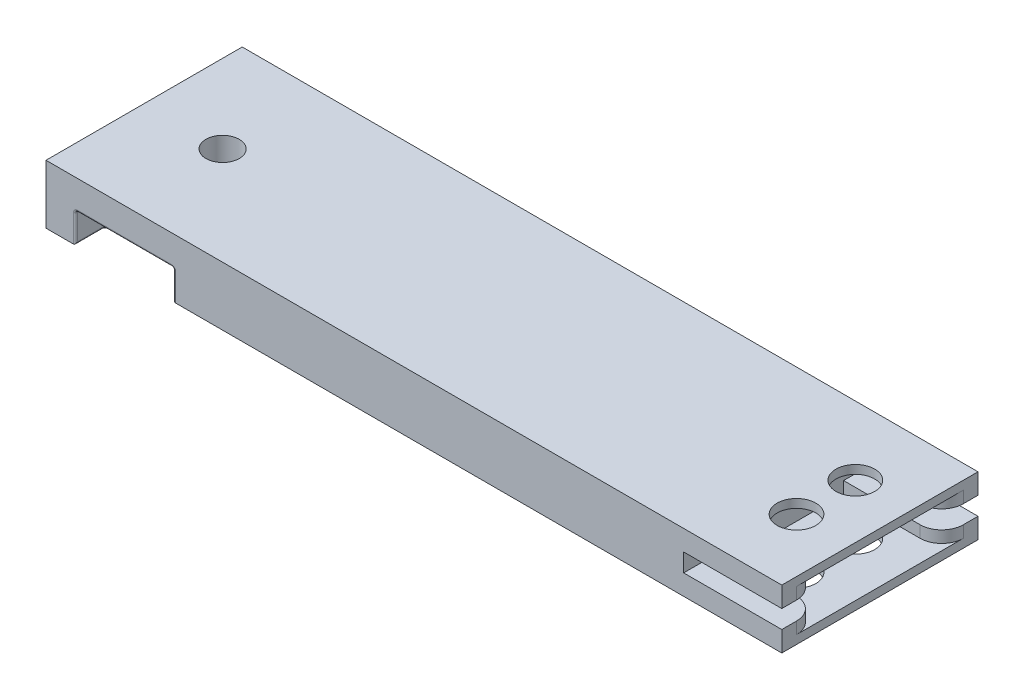
SolidWorks part; units mm, degrees
ref_plane "Front Plane" through (0, 0, 0) normal (0, 0, 1) x (1, 0, 0)
ref_plane "Top Plane" through (0, 0, 0) normal (0, 1, 0) x (1, 0, 0)
ref_plane "Right Plane" through (0, 0, 0) normal (1, 0, 0) x (0, 0, -1)
sketch "Sketch1" plane through (0, 0, 0) normal (1, 0, 0) x (0, 0, -1)
  line L1 (-10, -6) -> (10, -6)
  line L2 (-10, -6) -> (-10, 0)
  line L3 (-10, 0) -> (10, 0)
  line L4 (10, -6) -> (10, 0)
  line L5 (-10, -6) -> (10, 0) construction
  line L6 (-10, 0) -> (10, -6) construction
  point P0 (0, -3)
  dimension "D1" = 20
  dimension "D2" = 6
extrude "Boss-Extrude1" add sketch "Sketch1" along normal blind 75
hole_wizard "M3 Clearance Hole1" positions "Sketch2" profile "Sketch3" hole size "M3" standard "ISO" end condition through all
sketch "Sketch2" plane through (0, 0, 0) normal (0, 1, 0) x (1, 0, 0)
  line L0 (0, 10) -> (0, -10) construction
  point P0 (8, 0)
  dimension "D1" = 8
sketch "Sketch3" plane through (8, 0, 0) normal (1, 0, 0) x (0, 0, 1)
  line L0 (0, 0) -> (0, 6)
  line L1 (0, 6) -> (1.7, 6)
  line L2 (1.7, 6) -> (1.7, 0)
  line L5 (1.7, 0) -> (0, 0)
  line L11 (0, -6.35) -> (0, 107.95) construction
  dimension "Thru Hole Dia." = 3.4
  dimension "Thru Hole Depth" = 6
sketch "Sketch4" plane through (0, 0, 0) normal (0, 1, 0) x (1, 0, 0)
  line L13 (75, 10) -> (75, -10) construction
  circle A0 centre (69.5, 3) radius 1.975
  circle A1 centre (69.5, -3) radius 1.975
  point P10 (69.5, -3)
  point P18 (69.5, 3)
  dimension "D5" = 3.95
  dimension "D6" = 3.95
  dimension "D1" = 5.5
  dimension "D2" = 6
  dimension "D3" = 3
extrude "Cut-Extrude1" cut sketch "Sketch4" against normal through all
sketch "Sketch5" plane through (75, 0, 0) normal (1, 0, 0) x (0, 0, -1)
  line L0 (10, -6) -> (10, 0) construction
  line L1 (-10, -3.925) -> (-6.3, -3.925)
  line L2 (-10, -3.925) -> (-10, -2.075)
  line L3 (-10, -2.075) -> (-6.3, -2.075)
  line L4 (10, -3.925) -> (10, -2.075)
  line L7 (-10, 0) -> (-10, -6) construction
  line L8 (-6.3, -5.125) -> (6.3, -5.125)
  line L9 (-6.3, -5.125) -> (-6.3, -3.925)
  line L10 (-6.3, -0.875) -> (6.3, -0.875)
  line L11 (6.3, -5.125) -> (6.3, -3.925)
  line L15 (-6.3, -2.075) -> (-6.3, -0.875)
  line L18 (6.3, -2.075) -> (10, -2.075)
  line L20 (6.3, -3.925) -> (10, -3.925)
  line L21 (6.3, -2.075) -> (6.3, -0.875)
  point P0 (0, -3)
  point P7 (0, -3)
  point P12 (10, -3)
  point P17 (-10, -3)
  dimension "D1" = 12.6
  dimension "D2" = 1.85
  dimension "D3" = 3
  dimension "D4" = 4.25
extrude "Cut-Extrude2" cut sketch "Sketch5" against normal blind 10
sketch "Sketch6" plane through (0, -6, 0) normal (0, -1, 0) x (1, 0, 0)
  line L0 (75, 10) -> (0, 10) construction
  line L1 (3, 10) -> (13, 10)
  line L2 (3, 10) -> (3, 7)
  line L3 (3, 7) -> (13, 7)
  line L4 (13, 10) -> (13, 7)
  line L5 (75, -10) -> (0, -10) construction
  line L6 (13, -10) -> (3, -10)
  line L7 (13, -10) -> (13, -7)
  line L8 (13, -7) -> (3, -7)
  line L9 (3, -10) -> (3, -7)
  line L10 (0, 10) -> (0, -10) construction
  dimension "D1" = 3
  dimension "D2" = 10
  dimension "D3" = 3
extrude "Cut-Extrude3" cut sketch "Sketch6" against normal blind 3
fillet "Fillet1" radius 0.2 22 edges at (13, -6, -8.5) (3, -6, -8.5) (3, -4.5, -10) (13, -4.5, -10) (13, -4.5, -7) (3, -4.5, -7) (8, -6, -7) (8, -3, -10) (3, -3, -8.5) (8, -3, -7) (13, -3, -8.5) (3, -6, 8.5) (13, -6, 8.5) (13, -4.5, 10) (3, -4.5, 10) (3, -4.5, 7) (13, -4.5, 7) (8, -6, 7) (8, -3, 10) (13, -3, 8.5) (8, -3, 7) (3, -3, 8.5)
fillet "Fillet2" radius 2.2 4 edges at (75, -4.525, -6.3) (75, -4.525, 6.3) (75, -1.475, -6.3) (75, -1.475, 6.3)
sketch "Sketch7" plane through (0, -6, 0) normal (0, -1, 0) x (1, 0, 0)
  line L9 (2.55, 10) -> (13.45, 10)
  line L10 (0, 0) -> (75, 0) construction
  line L12 (13.45, 10) -> (13.45, 7.2)
  line L13 (12.8, 6.55) -> (3.2, 6.55)
  line L14 (2.55, 7.2) -> (2.55, 10)
  line L15 (13.45, 10) -> (13.45, 7.2)
  line L16 (12.8, 6.55) -> (3.2, 6.55)
  line L17 (2.55, 7.2) -> (2.55, 10)
  line L18 (2.55, -7.2) -> (2.55, -10)
  line L19 (12.8, -6.55) -> (3.2, -6.55)
  line L20 (13.45, -10) -> (13.45, -7.2)
  line L21 (2.55, -10) -> (13.45, -10)
  arc A6 (2.55, -7.2) -> (3.2, -6.55) centre (3.2, -7.2) cw
  arc A7 (12.8, -6.55) -> (13.45, -7.2) centre (12.8, -7.2) cw
  arc A8 (12.8, 6.55) -> (13.45, 7.2) centre (12.8, 7.2) ccw
  arc A9 (2.55, 7.2) -> (3.2, 6.55) centre (3.2, 7.2) ccw
  arc A10 (12.8, 6.55) -> (13.45, 7.2) centre (12.8, 7.2) ccw
  arc A11 (2.55, 7.2) -> (3.2, 6.55) centre (3.2, 7.2) ccw
  dimension "D1" = 0.25
extrude "3DP" [suppressed] cut sketch "Sketch7" against normal blind 3.5
fillet "3DP2" [suppressed] radius 0.2
sketch "Sketch8" [suppressed] plane through (0, 0, 0) normal (0, 1, 0) x (1, 0, 0)
  circle A2 centre (8, 0) radius 1.95
  circle A3 centre (8, 0) radius 1.95
  circle A10 centre (69.5, 3) radius 2.225
  circle A11 centre (69.5, 3) radius 2.225
  circle A13 centre (69.5, -3) radius 2.225
  circle A14 centre (69.5, -3) radius 2.225
  dimension "D1" = 0.25
  dimension "D2" = 0.25
  dimension "D3" = 0.25
extrude "3DP3" [suppressed] cut sketch "Sketch8" against normal through all
sketch "Sketch9" [suppressed] plane through (75, 0, 0) normal (1, 0, 0) x (0, 0, -1)
  line L3 (-6.3, -0.875) -> (-6.3, -2.075) construction
  line L10 (-10, -2.075) -> (-6.3, -2.075)
  line L11 (-6.3, -2.075) -> (-10, -2.075) construction
  line L12 (-6.3, -2.075) -> (-6.3, -0.875)
  line L13 (-6.3, -0.875) -> (6.3, -0.875)
  line L14 (8.5, -0.875) -> (-8.5, -0.875) construction
  line L15 (6.3, -0.875) -> (8.5, -0.875) construction
  line L16 (6.3, -0.875) -> (6.3, -2.075)
  line L17 (6.3, -2.075) -> (10, -2.075)
  line L18 (10, -2.075) -> (10, -3.925)
  line L19 (10, -3.925) -> (6.3, -3.925)
  line L20 (6.3, -3.925) -> (6.3, -5.125)
  line L21 (-8.5, -5.125) -> (8.5, -5.125) construction
  line L22 (6.3, -5.125) -> (6.3, -3.925) construction
  line L23 (6.3, -5.125) -> (-6.3, -5.125)
  line L24 (-6.3, -5.125) -> (-8.5, -5.125) construction
  line L25 (-6.3, -5.125) -> (-6.3, -3.925)
  line L26 (-6.3, -3.925) -> (-10, -3.925)
  line L27 (-10, -3.925) -> (-10, -2.075)
  line L28 (-10.35, -1.725) -> (-6.65, -1.725)
  line L29 (-6.65, -1.725) -> (-6.65, -0.525)
  line L30 (-6.65, -0.525) -> (6.65, -0.525)
  line L31 (6.65, -0.525) -> (6.65, -1.725)
  line L32 (6.65, -1.725) -> (10.35, -1.725)
  line L33 (10.35, -1.725) -> (10.35, -4.275)
  line L34 (10.35, -4.275) -> (6.65, -4.275)
  line L35 (6.65, -4.275) -> (6.65, -5.475)
  line L36 (6.65, -5.475) -> (-6.65, -5.475)
  line L37 (-6.65, -5.475) -> (-6.65, -4.275)
  line L38 (-6.65, -4.275) -> (-10.35, -4.275)
  line L39 (-10.35, -4.275) -> (-10.35, -1.725)
  line M13 (-8.5, -0.875) -> (8.5, -0.875)
  line M15 (8.5, -2.075) -> (10, -2.075)
  line M19 (-10, -2.075) -> (-8.5, -2.075)
  dimension "D1" = 0.35
extrude "3DP4" [suppressed] cut sketch "Sketch9" against normal blind 10.55 contours L27 L26 L25 L23 L20 L19 L18 L17 L16 L12 L10 M15 M13 M19
sketch "Sketch10" plane through (0, -5.125, 0) normal (0, 1, 0) x (1, 0, 0)
  line L0 (72.8, 6.5) -> (64.8, 6.5)
  line L1 (64.8, 6.5) -> (64.8, -6.5)
  line L2 (64.8, -6.5) -> (72.8, -6.5)
  line L3 (74.8, 8.5) -> (75, 8.5)
  line L4 (75, -8.5) -> (75, 8.5)
  line L5 (72.8, 6.3) -> (65, 6.3)
  line L6 (65, 6.3) -> (65, -6.3)
  line L7 (65, -6.3) -> (72.8, -6.3)
  line L9 (72.8, 6.3) -> (65, 6.3)
  line L11 (65, -6.3) -> (72.8, -6.3)
  line L12 (75, -8.5) -> (74.8, -8.5)
  line L17 (65, 6.3) -> (65, -6.3) construction
  line L18 (65, 6.3) -> (65, -6.3)
  arc A0 (72.8, 6.5) -> (74.8, 8.5) centre (72.8, 8.5) ccw
  arc A1 (74.8, -8.5) -> (72.8, -6.5) centre (72.8, -8.5) ccw
  arc A2 (72.8, 6.3) -> (75, 8.5) centre (72.8, 8.5) ccw
  arc A3 (75, -8.5) -> (72.8, -6.3) centre (72.8, -8.5) ccw
  arc A4 (72.8, 6.3) -> (75, 8.5) centre (72.8, 8.5) ccw
  arc A5 (75, -8.5) -> (72.8, -6.3) centre (72.8, -8.5) ccw
  dimension "D1" = 0
  dimension "D2" = 0.2
extrude "3DP5" [suppressed] cut sketch "Sketch10" along normal up to surface (4.25 mm away)
